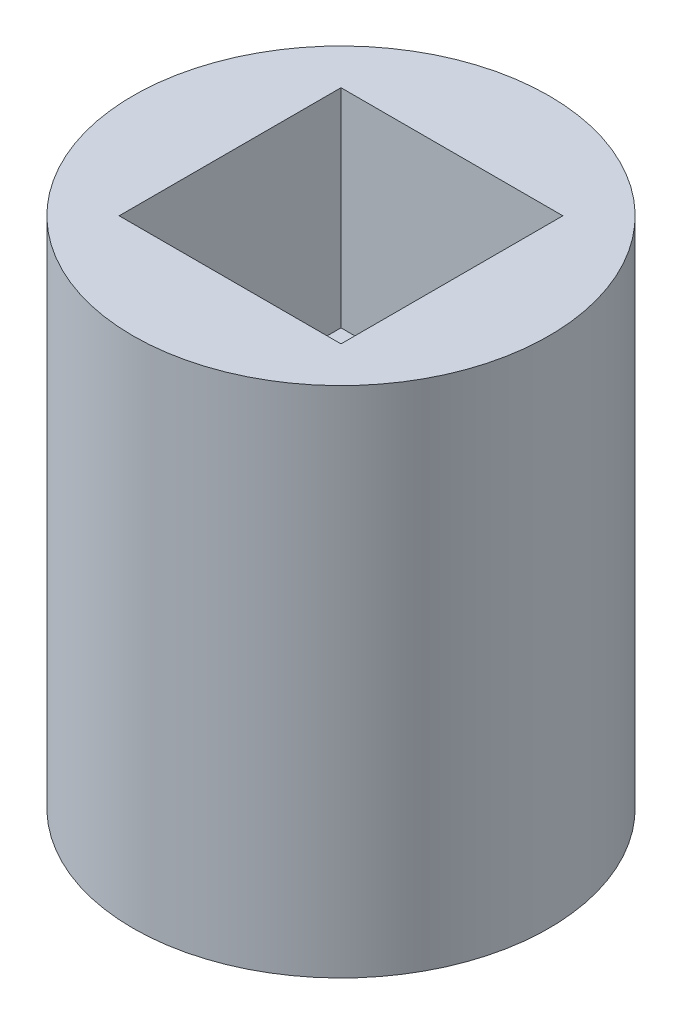
SolidWorks part; units mm, degrees
ref_plane "Front Plane" through (0, 0, 0) normal (0, 0, 1) x (1, 0, 0)
ref_plane "Top Plane" through (0, 0, 0) normal (0, 1, 0) x (1, 0, 0)
ref_plane "Right Plane" through (0, 0, 0) normal (1, 0, 0) x (0, 0, -1)
sketch "Sketch1" plane through (0, 0, 0) normal (0, 1, 0) x (1, 0, 0)
  circle A0 centre (0, 0) radius 4.08
  circle A1 centre (0, 0) radius 6.5
extrude "Boss-Extrude1" add sketch "Sketch1" along normal blind 20
sketch "Sketch2" plane through (0, 20, 0) normal (0, 1, 0) x (1, 0, 0)
  circle A0 centre (0, 0) radius 15
extrude "Boss-Extrude2" add sketch "Sketch2" along normal blind 2
sketch "Sketch3" plane through (0, 22, 0) normal (0, 1, 0) x (1, 0, 0)
  line L0 (-8, 8) -> (-8, -8)
  line L1 (-8, -8) -> (8, -8)
  line L2 (8, -8) -> (8, 8)
  line L3 (8, 8) -> (-8, 8)
  arc A0 (5.3852, -14) -> (-5.3852, -14) centre (0, 0) ccw
  circle A1 centre (0, 0) radius 15
  circle M8 centre (0, 0) radius 15
extrude "Boss-Extrude3" add sketch "Sketch3" along normal blind 15 contours L3 L2 L1 L0 M8
sketch "Sketch4" plane through (0, 20, 0) normal (0, -1, 0) x (1, 0, 0)
  circle A0 centre (0, 0) radius 6.5
  circle A1 centre (0, 0) radius 15
extrude "Boss-Extrude4" add sketch "Sketch4" along normal up to surface (20 mm away) up to face at (0, 0, 6.5)
sketch "Sketch6" plane through (0, 0, 0) normal (0, 0, 1) x (1, 0, 0)
  line L0 (-4.08, 20) -> (4.08, 20) construction
  line L1 (-4.08, 20) -> (4.08, 20)
  line L2 (0, 20) -> (0, 6)
  circle A0 centre (0, 6) radius 1
extrude "Cut-Extrude1" cut sketch "Sketch6" against normal blind 24
ref_plane "Plane1" through (0, 0, -6.5) normal (0, 0, 1) x (1, 0, 0)
ref_plane "Plane2" through (0, 0, -16.5) normal (0, 0, 1) x (1, 0, 0)
sketch "Sketch8" plane through (0, 0, -16.5) normal (0, 0, 1) x (1, 0, 0)
  circle A0 centre (0, 6) radius 1 construction
  circle A1 centre (0, 6) radius 1
  circle A2 centre (0, 6) radius 3
extrude "Cut-Extrude2" cut sketch "Sketch8" along normal blind 10 contours A1 | A2
chamfer "Chamfer1" distance 2 angle 45 1 edges at (0, 0, 4.08)
